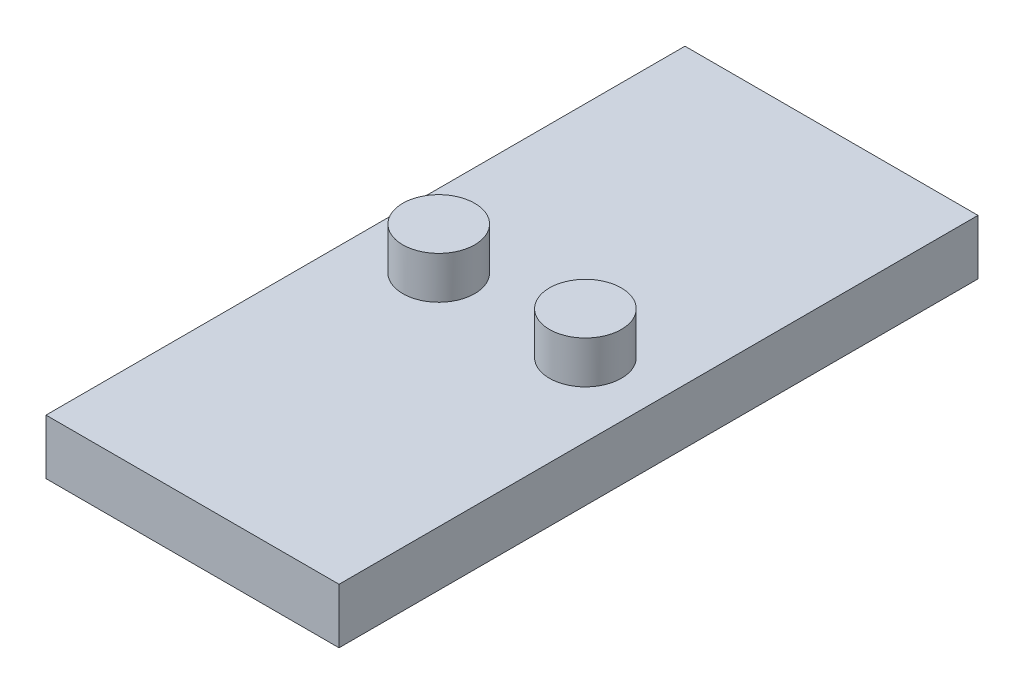
SolidWorks part; units mm, degrees
ref_plane "Front Plane" through (0, 0, 0) normal (0, 0, 1) x (1, 0, 0)
ref_plane "Top Plane" through (0, 0, 0) normal (0, 1, 0) x (1, 0, 0)
ref_plane "Right Plane" through (0, 0, 0) normal (1, 0, 0) x (0, 0, -1)
sketch "Sketch1" plane through (0, 0, 0) normal (0, 1, 0) x (1, 0, 0)
  line L1 (34.6, 75.442) -> (-34.6, 75.442)
  line L2 (34.6, 75.442) -> (34.6, -75.442)
  line L3 (34.6, -75.442) -> (-34.6, -75.442)
  line L4 (-34.6, 75.442) -> (-34.6, -75.442)
  line L5 (34.6, 75.442) -> (-34.6, -75.442) construction
  line L6 (34.6, -75.442) -> (-34.6, 75.442) construction
  point P0 (0, 0)
extrude "Boss-Extrude1" add sketch "Sketch1" along normal blind 13
sketch "Sketch2" plane through (0, 13, 0) normal (0, 1, 0) x (1, 0, 0)
  line L1 (-34.6, 75.442) -> (-34.6, -75.442) construction
  line L2 (34.6, -75.442) -> (34.6, 75.442) construction
  line L3 (0, 0) -> (-34.6, 0)
  line L4 (0.0502, 0.0185) -> (34.6, 0)
  circle A0 centre (-17.3, 0) radius 8.495
  circle A1 centre (17.3251, 0.0093) radius 8.495
  point P12 (17.3251, 0.0093)
  point P13 (0, 0)
  point P14 (0, 0)
  dimension "D1" = 16.99
  dimension "D2" = 34.6251
extrude "Boss-Extrude2" add sketch "Sketch2" along normal blind 10 contours L3 A0 | L4 A1 | L4 A1
